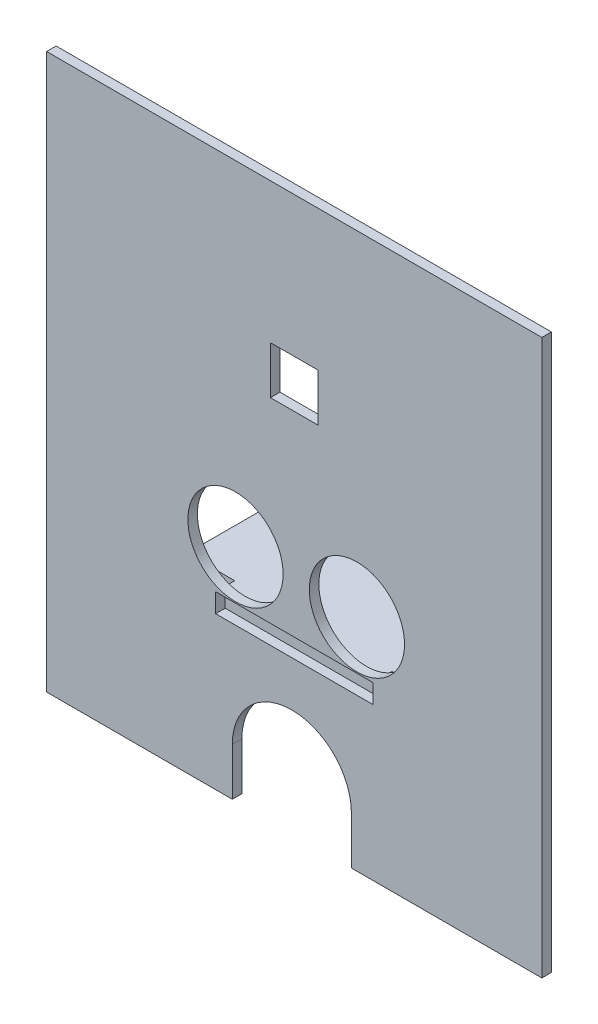
SolidWorks part; units mm, degrees
other "초음파센서받침대"
ref_plane "정면" through (0, 0, 0) normal (0, 0, 1) x (1, 0, 0)
ref_plane "윗면" through (0, 0, 0) normal (0, 1, 0) x (1, 0, 0)
ref_plane "우측면" through (0, 0, 0) normal (1, 0, 0) x (0, 0, -1)
sketch "스케치1" plane through (0, 0, 0) normal (0, 0, 1) x (1, 0, 0)
  line L1 (-52, 5) -> (52, 5)
  line L2 (-52, 5) -> (-52, 121.5)
  line L3 (-52, 121.5) -> (52, 121.5)
  line L4 (52, 5) -> (52, 121.5)
  dimension "D1" = 116.5
extrude "보스-돌출1" add sketch "스케치1" along normal blind 2
sketch "스케치3" plane through (0, 0, 2) normal (0, 0, 1) x (1, 0, 0)
  line L0 (-13, 15) -> (-13, 5)
  line L1 (-52, 5) -> (52, 5) construction
  line L2 (12, 15) -> (12, 5)
  line L3 (-13, 5) -> (12, 5)
  arc A0 (12, 15) -> (-13, 15) centre (-0.5, 15) ccw
  dimension "D1" = 25
extrude "컷-돌출1" cut sketch "스케치3" against normal blind 4
sketch "스케치4" plane through (0, 0, 0) normal (0, 0, -1) x (-1, 0, 0)
  line L0 (-52, 5) -> (-52, 121.5) construction
  line L1 (-22.5, 61.5) -> (22.5, 61.5)
  line L2 (-22.5, 61.5) -> (-22.5, 41)
  line L3 (-22.5, 41) -> (22.5, 41)
  line L4 (22.5, 61.5) -> (22.5, 41)
  line L5 (-52, 121.5) -> (52, 121.5) construction
  dimension "D1" = 45
  dimension "D2" = 20.5
  dimension "D3" = 29.5
  dimension "D4" = 60
sketch "스케치5" plane through (0, 0, 0) normal (0, 0, -1) x (-1, 0, 0)
  line L0 (-22.5, 41) -> (22.5, 41) construction
  line L1 (-26.5, 41) -> (26.5, 41)
  line L2 (-26.5, 41) -> (-26.5, 37)
  line L3 (-26.5, 37) -> (26.5, 37)
  line L4 (26.5, 41) -> (26.5, 37)
  line L5 (-22.5, 61.5) -> (-22.5, 41) construction
  dimension "D1" = 4
  dimension "D2" = 53
  dimension "D3" = 4
extrude "보스-돌출2" add sketch "스케치5" along normal blind 20 separate body
sketch "스케치6" plane through (0, 41, 0) normal (0, 1, 0) x (1, 0, 0)
  line L0 (26.5, 20) -> (26.5, 0) construction
  line L1 (26.5, 2) -> (16.5, 2)
  line L2 (26.5, 2) -> (26.5, 0)
  line L3 (26.5, 0) -> (16.5, 0)
  line L4 (16.5, 2) -> (16.5, 0)
  line L5 (52, 0) -> (-52, 0) construction
  line L7 (-26.5, 0) -> (-16.5, 0)
  line L8 (-26.5, 0) -> (-26.5, 2)
  line L9 (-26.5, 2) -> (-16.5, 2)
  line L10 (-16.5, 0) -> (-16.5, 2)
  dimension "D1" = 2
  dimension "D2" = 10
  dimension "D3" = 2
  dimension "D4" = 10
extrude "컷-돌출2" cut sketch "스케치6" against normal blind 20
sketch "스케치8" plane through (0, 0, 2) normal (0, 0, 1) x (1, 0, 0)
  line L0 (22.5, 41) -> (-22.5, 41) construction
  line L1 (-16.4982, 41) -> (16.5018, 41)
  line L2 (-16.4982, 41) -> (-16.4982, 37)
  line L3 (-16.4982, 37) -> (16.5018, 37)
  line L4 (16.5018, 41) -> (16.5018, 37)
  dimension "D1" = 33
  dimension "D2" = 4
extrude "컷-돌출3" cut sketch "스케치8" against normal blind 2
sketch "스케치9" plane through (0, 0, 2) normal (0, 0, 1) x (1, 0, 0)
  circle A0 centre (-12.34, 51.25) radius 10
  circle A1 centre (13.16, 51.25) radius 10
  dimension "D1" = 20
  dimension "D2" = 20
extrude "컷-돌출4" cut sketch "스케치9" against normal blind 2
sketch "스케치10" plane through (0, 0, 0) normal (0, 0, -1) x (-1, 0, 0)
  line L0 (-52, 5) -> (-52, 121.5) construction
  line L1 (-12.5, 96.5) -> (12.5, 96.5)
  line L2 (-12.5, 96.5) -> (-12.5, 72.5)
  line L3 (-12.5, 72.5) -> (12.5, 72.5)
  line L4 (12.5, 96.5) -> (12.5, 72.5)
  line L5 (-52, 121.5) -> (52, 121.5) construction
  line L6 (5, 92.05) -> (5, 82.05)
  line L7 (12.5, 96.5) -> (4.25, 96.5)
  line L8 (12.5, 96.5) -> (12.5, 91.3)
  line L9 (12.5, 91.3) -> (4.25, 91.3)
  line L10 (4.25, 96.5) -> (4.25, 91.3)
  line L11 (4.25, 91.3) -> (-4.25, 91.3)
  line L12 (4.25, 91.3) -> (4.25, 82.8)
  line L13 (4.25, 82.8) -> (-4.25, 82.8)
  line L14 (-4.25, 91.3) -> (-4.25, 82.8)
  line L15 (5, 82.05) -> (-5, 82.05)
  line L16 (-5, 92.05) -> (-5, 82.05)
  line L17 (5, 92.05) -> (-5, 92.05)
  dimension "D1" = 25
  dimension "D2" = 24
  dimension "D3" = 39.5
  dimension "D4" = 25
  dimension "D5" = 8.25
  dimension "D6" = 5.2
  dimension "D7" = 8.5
  dimension "D8" = 8.5
  dimension "D9" = 0.75
extrude "컷-돌출5" cut sketch "스케치10" against normal blind 2 contours L10 L17 L16 L15 L6 L9 L12 L13 L14 L11 | L11 L14 L13 L12 | L6 L17 L10 L9
other "바디 저장1"
other "바디 저장2"
